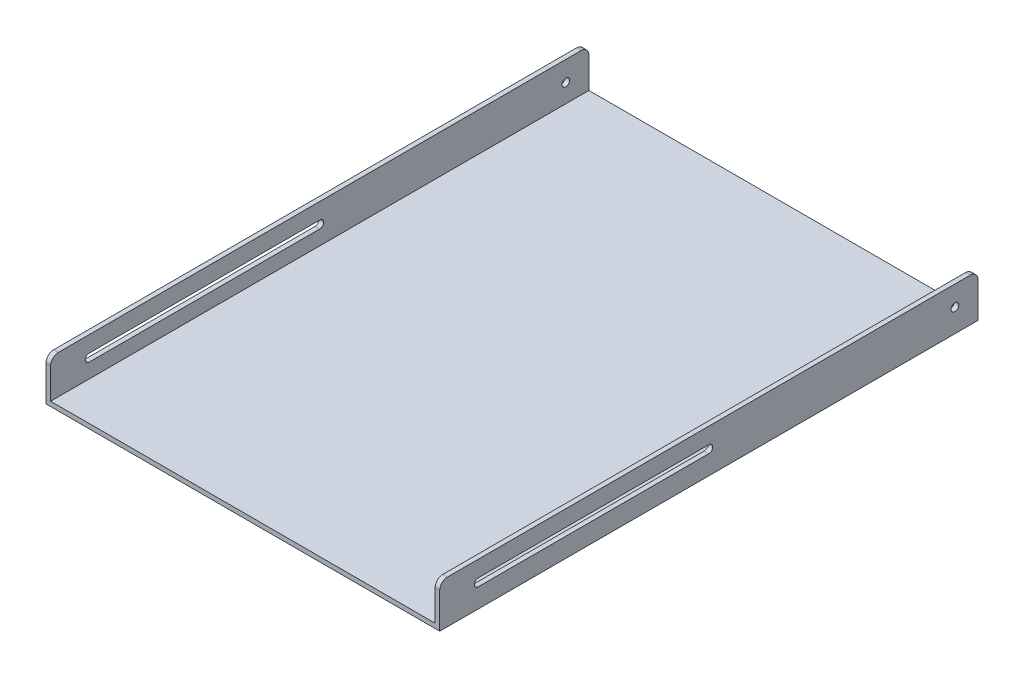
SolidWorks part; units mm, degrees
ref_plane "Front Plane" through (0, 0, 0) normal (0, 0, 1) x (1, 0, 0)
ref_plane "Top Plane" through (0, 0, 0) normal (0, 1, 0) x (1, 0, 0)
ref_plane "Right Plane" through (0, 0, 0) normal (1, 0, 0) x (0, 0, -1)
sketch "Sketch1" plane through (0, 0, 0) normal (0, 0, 1) x (1, 0, 0)
  line L0 (-250, 50) -> (-250, 0)
  line L1 (-250, 0) -> (250, 0)
  line L2 (250, 0) -> (250, 50)
  dimension "D1" = 500
  dimension "D2" = 250
  dimension "D3" = 50
  dimension "D4" = 50
extrude "Extrude-Thin1" add sketch "Sketch1" along normal mid plane 700 thin
sketch "Sketch2" plane through (256, 0, 0) normal (1, 0, 0) x (0, 0, -1)
  line L0 (-300, 24) -> (0, 24) construction
  line L1 (-300, 29) -> (0, 29)
  line L2 (-300, 19) -> (0, 19)
  line L3 (-350, -6) -> (350, -6) construction
  line L4 (350, -6) -> (350, 50) construction
  circle A0 centre (320, 24) radius 5
  arc A1 (-300, 29) -> (-300, 19) centre (-300, 24) ccw
  arc A2 (0, 19) -> (0, 29) centre (0, 24) ccw
  point P4 (-150, 24)
  dimension "D1" = 10
  dimension "D2" = 30
  dimension "D3" = 30
  dimension "D4" = 150
  dimension "D5" = 300
  dimension "D6" = 10
extrude "Cut-Extrude1" cut sketch "Sketch2" against normal through all
fillet "Fillet1" radius 10 4 edges at (253, 50, 350) (-253, 50, 350) (-253, 50, -350) (253, 50, -350)
